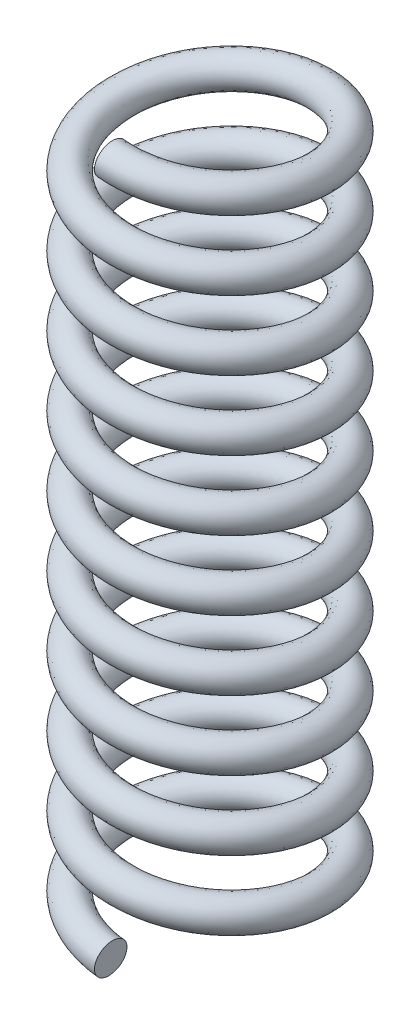
SolidWorks part; units mm, degrees
ref_plane "Front Plane" through (0, 0, 0) normal (0, 0, 1) x (1, 0, 0)
ref_plane "Top Plane" through (0, 0, 0) normal (0, 1, 0) x (1, 0, 0)
ref_plane "Right Plane" through (0, 0, 0) normal (1, 0, 0) x (0, 0, -1)
sketch "Sketch1" plane through (0, 0, 0) normal (0, 1, 0) x (1, 0, 0)
  circle A0 centre (0, 0) radius 2.15
  dimension "D1" = 4.3
curve "Helix/Spiral1" pitch 1.5 height 15 turns 10
sweep "Sweep2" add path "Helix/Spiral1" circular profile diameter 0.7 parameters "D3"=0.7
